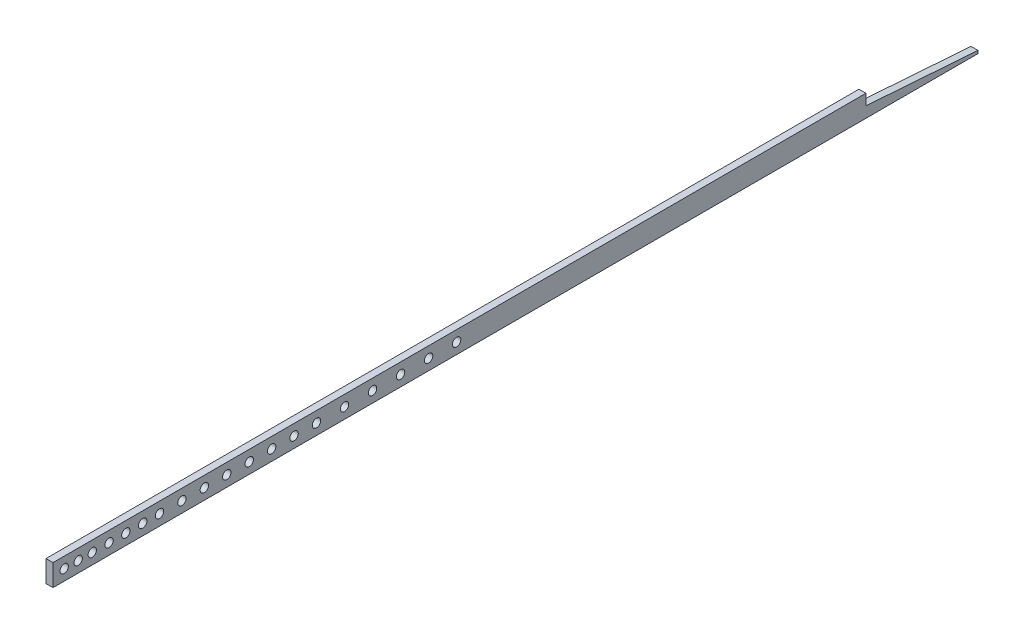
SolidWorks part; units mm, degrees
ref_plane "Ebene vorne" through (0, 0, 0) normal (0, 0, 1) x (1, 0, 0)
ref_plane "Ebene oben" through (0, 0, 0) normal (0, 1, 0) x (1, 0, 0)
ref_plane "Ebene rechts" through (0, 0, 0) normal (1, 0, 0) x (0, 0, -1)
sketch "Skizze1" plane through (0, 0, 0) normal (0, 0, 1) x (1, 0, 0)
  line L1 (0, 0) -> (5, 0)
  line L2 (0, 0) -> (0, 15.5)
  line L3 (0, 15.5) -> (5, 15.5)
  line L4 (5, 0) -> (5, 15.5)
  dimension "D1" = 5
  dimension "D2" = 15.5
extrude "GrundStab" add sketch "Skizze1" along normal blind 580
sketch "Skizze2" plane through (0, 0, 0) normal (-1, 0, 0) x (0, 0, 1)
  line L0 (0, 15.5) -> (0, 7.75)
  line L1 (0, 15.5) -> (0, 0) construction
  line L3 (580, 15.5) -> (0, 15.5) construction
  line L4 (80, 15.5) -> (0, 15.5)
  line L5 (80, 15.5) -> (80, 13.5)
  line L6 (80, 13.5) -> (0, 7.75)
  dimension "D1" = 80
  dimension "D2" = 2
extrude "SchäftungInnen" [suppressed] cut sketch "Skizze2" against normal through all
sketch "Skizze3" plane through (0, 0, 0) normal (-1, 0, 0) x (0, 0, 1)
  line L0 (0, 7.75) -> (-80, 2)
  line L1 (0, 15.5) -> (0, 0) construction
  line L2 (-80, 2) -> (-80, 0)
  line L3 (-80, 0) -> (0, 0)
  line L4 (0, 0) -> (0, 7.75)
  dimension "D1" = 2
  dimension "D2" = 80
extrude "Aufsatz-Linear austragen2" add sketch "Skizze3" against normal through all
sketch "Skizze4" plane through (0, 0, 0) normal (-1, 0, 0) x (0, 0, 1)
  line L0 (580, 7.75) -> (572, 7.75) construction
  line L1 (580, 15.5) -> (580, 0) construction
  circle A0 centre (572, 7.75) radius 3
  circle A1 centre (562, 7.75) radius 3
  circle A2 centre (552, 7.75) radius 3
  circle A3 centre (540, 7.75) radius 3
  circle A4 centre (528, 7.75) radius 3
  circle A5 centre (516, 7.75) radius 3
  circle A6 centre (504, 7.75) radius 3
  circle A7 centre (488, 7.75) radius 3
  circle A8 centre (472, 7.75) radius 3
  circle A9 centre (456, 7.75) radius 3
  circle A10 centre (440, 7.75) radius 3
  circle A11 centre (424, 7.75) radius 3
  circle A12 centre (408, 7.75) radius 3
  circle A13 centre (392, 7.75) radius 3
  circle A14 centre (372, 7.75) radius 3
  circle A15 centre (352, 7.75) radius 3
  circle A16 centre (332, 7.75) radius 3
  circle A17 centre (312, 7.75) radius 3
  circle A18 centre (292, 7.75) radius 3
  dimension "D1" = 6
  dimension "D2" = 8
  dimension "D3" = 3
  dimension "D4" = 5
  dimension "D5" = 8
  dimension "D6" = 6
extrude "Schnitt-Linear austragen1" cut sketch "Skizze4" against normal through all
